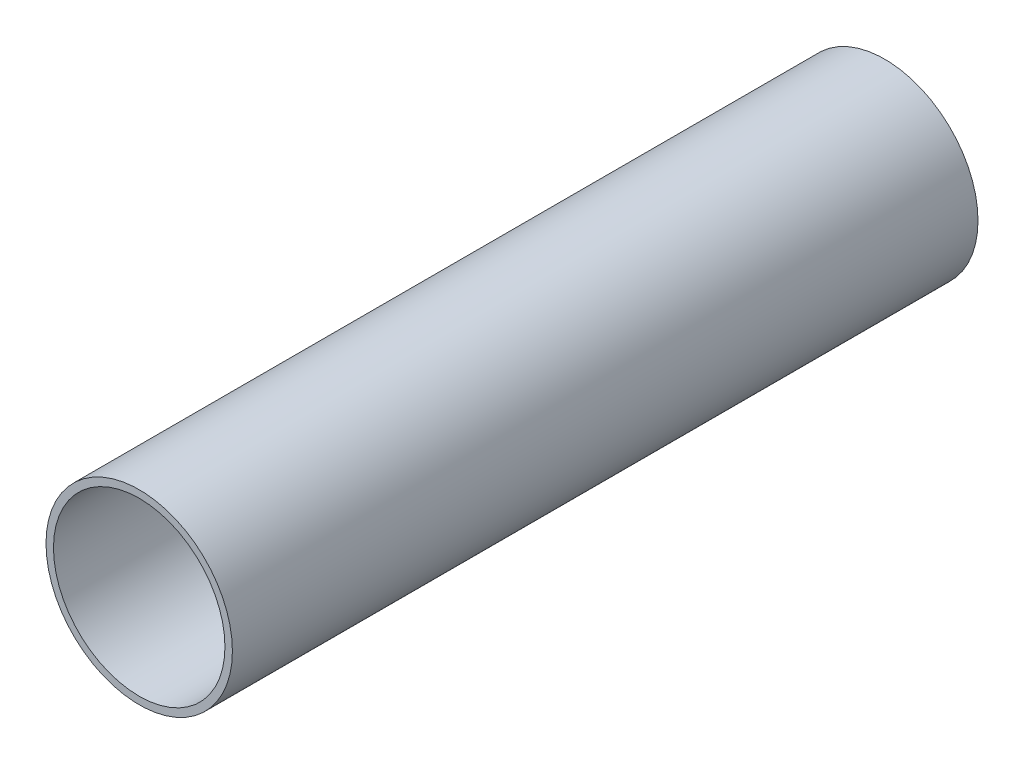
SolidWorks part; units mm, degrees
ref_plane "Ön Düzlem" through (0, 0, 0) normal (0, 0, 1) x (1, 0, 0)
ref_plane "Üst Düzlem" through (0, 0, 0) normal (0, 1, 0) x (1, 0, 0)
ref_plane "Sağ Düzlem" through (0, 0, 0) normal (1, 0, 0) x (0, 0, -1)
sketch "Sketch1" plane through (0, 0, 0) normal (0, 0, 1) x (1, 0, 0)
  circle A0 centre (0, 0) radius 12.5
  circle A1 centre (0, 0) radius 11.5
  dimension "D1" = 23
  dimension "25" = 25
extrude "Boss-Extrude1" add sketch "Sketch1" along normal blind 100
